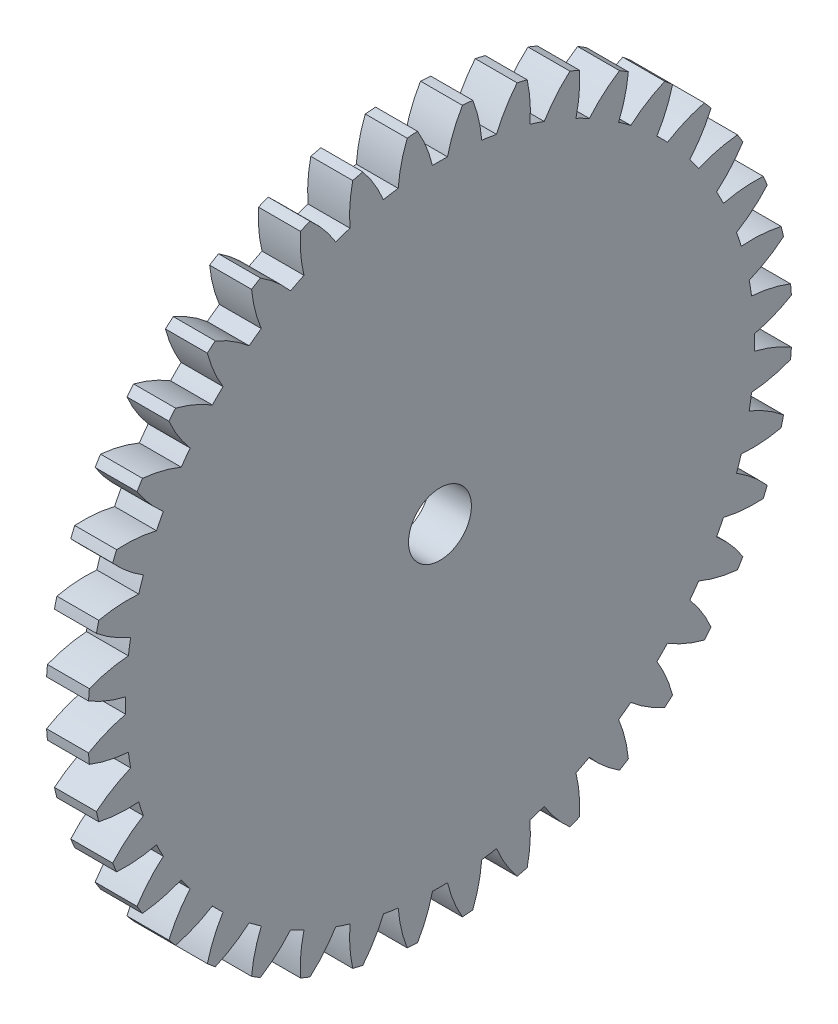
SolidWorks part; units mm, degrees
ref_plane "Plane1" through (0, 0, 0) normal (0, 0, 1) x (1, 0, 0)
ref_plane "Plane2" through (0, 0, 0) normal (0, 1, 0) x (1, 0, 0)
ref_plane "Plane3" through (0, 0, 0) normal (1, 0, 0) x (0, 0, -1)
sketch "HoldingSke" plane through (0, 0, 0) normal (0, 1, 0) x (1, 0, 0)
  line L0 (0, 0) -> (0.9576, -0.8035)
  line L1 (-15, 0) -> (100, 0) construction
  line L2 (0, 0) -> (-2.1039, 2.3779)
  line L3 (0, 0) -> (-11.863, 4.5341)
  line L4 (0, 0) -> (6.6156, 5.5511)
  line L5 (0, 0) -> (-46.8476, -17.4728)
  line L6 (0, 0) -> (-1.6579, -1.1186)
  line L7 (-2.1039, 2.3779) -> (8.6586, 51.2059)
  line L8 (-76.2, 54.61) -> (-75.7, 54.61)
  line L9 (-71.009, 38.7566) -> (-53.1078, 45.2721)
  line L10 (-76.2, 71.12) -> (104.1128, 71.12)
  line L11 (0, 0) -> (-2, 0)
  line L12 (-76.2, 101.6) -> (-76.17, 101.6)
  line L13 (24.9733, 27.94) -> (52.9518, 28.4284)
  line L14 (24.9733, 27.94) -> (24.9743, 27.94)
  line L15 (24.9733, 27.94) -> (100.4006, 29.5858)
  line L16 (-63.627, -0.8) -> (-12.827, -0.8)
  circle A0 centre (0, 0) radius 1.5
  circle A1 centre (0, 0) radius 14.999
  circle A2 centre (0, 0) radius 37.5
  circle A3 centre (0, 0) radius 1.5
  dimension "MHD" = 29.998
  dimension "Hub_dia" = 75
  dimension "Bore" = 3
  dimension "MBD" = 3
  dimension "Num_teeth" = 40
  dimension "Pitch" = 1.25
  dimension "Overall_len" = 50
  dimension "Show_teeth" = 40
  dimension "Thickness" = 2
  dimension "OAL" = 50.0001
  dimension "T_dim" = 0.5
  dimension "Ap" = 20
  dimension "H" = 19.05
  dimension "Pitch_radius" = 180.3128
  dimension "Width" = 2
  dimension "Backlash" = 0.03
  dimension "Addendum_fac" = 1
  dimension "Dedendum_fac" = 1.25
  dimension "Clearance_fac" = 0.25
  dimension "Dedendum_add" = 0.001
  dimension "Module" = 0.8
sketch "BasProSke" plane through (0, 0, 0) normal (0, 1, 0) x (1, 0, 0)
  line L0 (-10, 0) -> (60, 0) construction
  line L1 (0, 0) -> (0, 16.8)
  line L2 (0, 0) -> (2, 0)
  line L3 (2, 0) -> (2, 16.8)
  line L4 (2, 16.8) -> (0, 16.8)
  dimension "Thickness" = 2
  dimension "Diameter" = 33.6
revolve "Base-Revolve" add sketch "BasProSke" angle 360 about L0
sketch "TooCutSke" plane through (0, 0, 0) normal (1, 0, 0) x (0, 0, -1)
  line L1 (0, 0) -> (0, 107) construction
  line L2 (0, 0) -> (-0.6807, 15.9855) construction
  line L3 (0, 0) -> (-2.5091, 31.8807) construction
  line L4 (-0.6807, 15.9855) -> (-1.2545, 15.9404) construction
  arc A0 (0.3582, 14.9947) -> (-0.3582, 14.9947) centre (0, 0) ccw
  arc A1 (1.086, 16.7903) -> (-1.086, 16.7903) centre (0, 0) ccw
  circle A2 centre (0, 0) radius 16 construction
  circle A3 centre (0, 0) radius 15.0351 construction
  arc A4 (-0.3582, 14.9947) -> (-1.086, 16.7903) centre (-6.5851, 13.5163) ccw
  arc A5 (1.086, 16.7903) -> (0.3582, 14.9947) centre (6.5851, 13.5163) ccw
  dimension "Root_dia" = 29.998
  dimension "Overcut_dia" = 33.6508
  dimension "Pitch_dia" = 32
  dimension "Base_dia" = 30.0702
  dimension "Flank_rad" = 6.4
  dimension "Half_ang" = 4.5
  dimension "Half_CT" = 0.5757
extrude "ToothCut" cut sketch "TooCutSke" along normal through all
fillet "Breaks" [suppressed] radius 0.016
fillet "RootFillets" [suppressed] radius 0.201
pattern_circular "TeethCuts" count 40 every 9 about axis through (-10, 0, 0) along (1, 0, 0) of "ToothCut", "RootFillets", "Breaks"
sketch "HubNeaOneSke" plane through (0, 0, 0) normal (-1, 0, 0) x (0, 0, 1)
  circle A0 centre (0, 0) radius 14.999
  dimension "Diameter" = 29.998
extrude "HubNearOne" [suppressed] add sketch "HubNeaOneSke" along normal blind 48.0001
sketch "HubNeaBotSke" plane through (0, 0, 0) normal (-1, 0, 0) x (0, 0, 1)
  circle A0 centre (0, 0) radius 14.999
  dimension "Diameter" = 29.998
extrude "HubNearBoth" [suppressed] add sketch "HubNeaBotSke" along normal blind 24
ref_plane "FarPln" through (2, 0, 0) normal (1, 0, 0) x (0, 0, -1)
sketch "HubFarSke" plane through (2, 0, 0) normal (1, 0, 0) x (0, 0, -1)
  circle A0 centre (0, 0) radius 14.999
  dimension "Diameter" = 29.998
extrude "HubFar" [suppressed] add sketch "HubFarSke" along normal blind 24
sketch "BorSke" plane through (0, 0, 0) normal (1, 0, 0) x (0, 0, -1)
  circle A0 centre (0, 0) radius 1.5
  dimension "Diameter" = 3
extrude "Bore" cut sketch "BorSke" along normal mid plane 100.0001
sketch "KeySke" plane through (0, 0, 0) normal (1, 0, 0) x (0, 0, -1)
  line L0 (-0.6, 0) -> (-0.6, 2)
  line L1 (-0.6, 2) -> (0.6, 2)
  line L2 (0.6, 2) -> (0.6, 0)
  line L3 (0, 0) -> (0, 34) construction
  line L4 (-0.6, 0) -> (0.6, 0)
  dimension "Offset" = 2
  dimension "Width" = 1.2
extrude "Keyway" [suppressed] cut sketch "KeySke" along normal mid plane 100.0001
pattern_circular "Keyway2" [suppressed] count 2 every 90 about axis through (-10, 0, 0) along (1, 0, 0)
equation "' \"Module@HoldingSke\" = 6.35"
equation "' \"Num_teeth@HoldingSke\" = 12"
equation "' \"Ap@HoldingSke\" =  20"
equation "' \"Ap@HoldingSke\" = 20"
equation "' \"Width@HoldingSke\" = 0.5 * 25.4"
equation "' \"Hub_dia@HoldingSke\"= 1 * 25.4"
equation "' \"Hub_dia@HoldingSke\" = 1 * 25.4"
equation "' \"Overall_len@HoldingSke\" = 1.0 * 25.4"
equation "' \"Bore@HoldingSke\" = 0.75 * 25.4"
equation "' \"T_dim@HoldingSke\" = 0.1 * 25.4"
equation "' \"Width@KeySke\" = 0.25 * 25.4"
equation "' \"Show_teeth@HoldingSke\" = 13"
equation "' \"Backlash@HoldingSke\" = 0.009 * 25.4"
equation "' \"Addendum_fac@HoldingSke\" = 1.0"
equation "' \"Dedendum_fac@HoldingSke\" = 1.25"
equation "' \"Dedendum_add@HoldingSke\" = 0.00005 * 25.4"
equation "' \"Clearance_fac@HoldingSke\" = 0.25"
equation "\"Pitch@HoldingSke\" = 1 / \"Module@HoldingSke\""
equation "\"Overcut_dia@TooCutSke\" = (\"Num_teeth@HoldingSke\" + 2 * \"Addendum_fac@HoldingSke\") / \"Pitch@HoldingSke\" + 0.002 * 25.4"
equation "\"Pitch_dia@TooCutSke\" = \"Num_teeth@HoldingSke\" / \"Pitch@HoldingSke\""
equation "\"Base_dia@TooCutSke\" = \"Num_teeth@HoldingSke\" / \"Pitch@HoldingSke\" * cos((\"Ap@HoldingSke\"  * 3.14159265 / 180))"
equation "\"Root_dia@TooCutSke\" = (\"Num_teeth@HoldingSke\" + 2) / \"Pitch@HoldingSke\" - 2 * (\"Addendum_fac@HoldingSke\" + \"Dedendum_fac@HoldingSke\") / \"Pitch@HoldingSke\" - \"Dedendum_add@HoldingSke\" * 2"
equation "\"Half_ang@TooCutSke\" = 180 / \"Num_teeth@HoldingSke\""
equation "\"Half_CT@TooCutSke\" = \"Num_teeth@HoldingSke\" / \"Pitch@HoldingSke\" * sin((3.14159265 / 2 / \"Num_teeth@HoldingSke\")) / 2 - 7 * \"Backlash@HoldingSke\" / 4"
equation "\"Flank_rad@TooCutSke\" = \"Num_teeth@HoldingSke\" / \"Pitch@HoldingSke\" / 5"
equation "\"Radius@RootFillets\" = \"Clearance_fac@HoldingSke\" / \"Pitch@HoldingSke\" + \"Dedendum_add@HoldingSke\""
equation "\"Break_rad@Breaks\" = 0.02 / \"Pitch@HoldingSke\""
equation "\"Thickness@HoldingSke\" = \"Width@HoldingSke\""
equation "\"OAL@HoldingSke\" = \"Thickness@HoldingSke\""
equation "\"MHD@HoldingSke\" = (\"Num_teeth@HoldingSke\" + 2) / \"Pitch@HoldingSke\" - 2 * (\"Addendum_fac@HoldingSke\" + \"Dedendum_fac@HoldingSke\")  / \"Pitch@HoldingSke\" - \"Dedendum_add@HoldingSke\" * 2"
equation "\"MBD@HoldingSke\" = (\"Num_teeth@HoldingSke\" + 2) / \"Pitch@HoldingSke\" - 2 * (\"Addendum_fac@HoldingSke\" + \"Dedendum_fac@HoldingSke\")  / \"Pitch@HoldingSke\" - \"Dedendum_add@HoldingSke\" * 2 - 0.002 * 25.4"
equation "\"MHD@HoldingSke\" = ((sgn( \"MHD@HoldingSke\" - \"Hub_dia@HoldingSke\" )-1)*( \"MHD@HoldingSke\" - \"Hub_dia@HoldingSke\" ))/-2+ \"Hub_dia@HoldingSke\""
equation "\"MBD@HoldingSke\" = ((sgn( \"MBD@HoldingSke\" - \"Bore@HoldingSke\" )-1)*( \"MBD@HoldingSke\" - \"Bore@HoldingSke\" ))/-2+ \"Bore@HoldingSke\""
equation "\"OAL@HoldingSke\" = ((sgn( \"OAL@HoldingSke\" - \"Overall_len@HoldingSke\" )+1)*( \"OAL@HoldingSke\" - \"Overall_len@HoldingSke\" ))/2 + \"Overall_len@HoldingSke\" + 0.000002 * 25.4"
equation "\"Num_teeth@TeethCuts\" = int( \"Show_teeth@HoldingSke\" ) + 1"
equation "\"Num_teeth@TeethCuts\" = ((sgn( \"Num_teeth@TeethCuts\" - \"Num_teeth@HoldingSke\" )-1)*( \"Num_teeth@TeethCuts\" - \"Num_teeth@HoldingSke\" ))/-2+ \"Num_teeth@HoldingSke\""
equation "\"Num_teeth@TeethCuts\" = ((sgn( \"Num_teeth@TeethCuts\" - 2.0)+1)*( \"Num_teeth@TeethCuts\" - 2.0))/2 +2.0"
equation "\"Angle@TeethCuts\" = 360.0 / \"Num_teeth@HoldingSke\""
equation "\"Diameter@BasProSke\" = (\"Num_teeth@HoldingSke\" + 2 * \"Addendum_fac@HoldingSke\") / \"Pitch@HoldingSke\""
equation "\"Thickness@BasProSke\"  = \"Thickness@HoldingSke\""
equation "' \"Fillet_rad@BasProSke\" =  \"Thickness@HoldingSke\" * 0.05"
equation "' \"Fillet_rad@BasProSke\" = \"Thickness@HoldingSke\" * 0.05"
equation "\"MHD@HoldingSke\" = ((sgn( \"MHD@HoldingSke\" - \"Root_dia@TooCutSke\" )-1)*( \"MHD@HoldingSke\" - \"Root_dia@TooCutSke\" ))/-2+ \"Root_dia@TooCutSke\""
equation "\"Diameter@HubNeaOneSke\" = \"MHD@HoldingSke\""
equation "\"Length@HubNearOne\" = \"OAL@HoldingSke\" - \"Thickness@BasProSke\""
equation "\"Diameter@HubNeaBotSke\" = \"MHD@HoldingSke\""
equation "\"Length@HubNearBoth\" = ( \"OAL@HoldingSke\" - \"Thickness@BasProSke\" ) / 2.0"
equation "\"Thickness@FarPln\" = \"Thickness@BasProSke\""
equation "\"Diameter@HubFarSke\" = \"MHD@HoldingSke\""
equation "\"Length@HubFar\" = ( \"OAL@HoldingSke\" - \"Thickness@BasProSke\" ) / 2.0"
equation "\"Diameter@BorSke\" = \"MBD@HoldingSke\""
equation "\"D1@Bore\" = \"OAL@HoldingSke\" * 2.0"
equation "\"D1@Keyway\" = \"OAL@HoldingSke\" * 2.0"
equation "\"Offset@KeySke\" = \"T_dim@HoldingSke\" + \"MBD@HoldingSke\" / 2.0"
